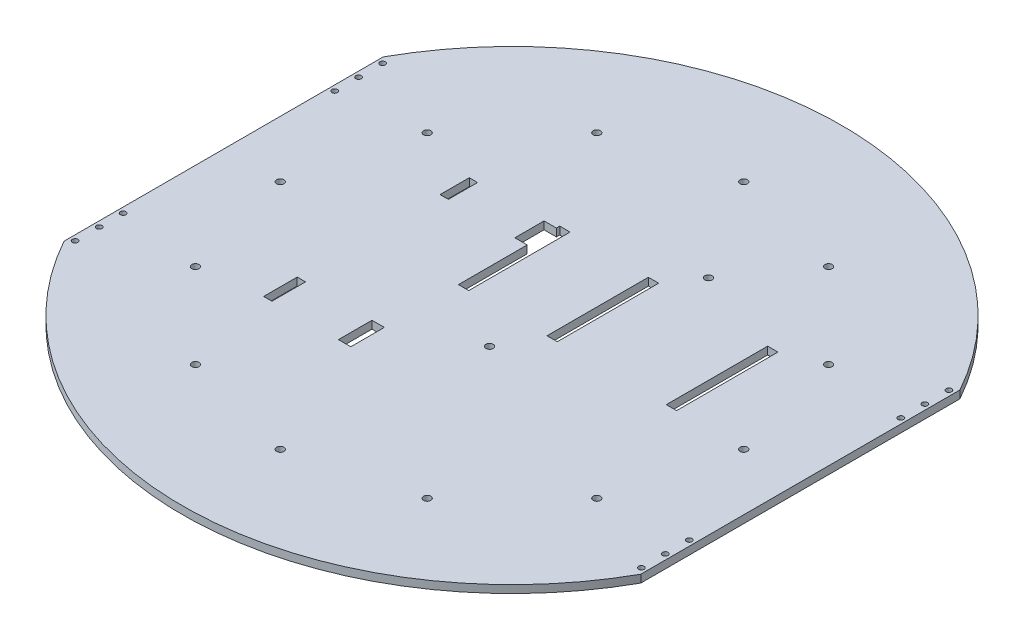
SolidWorks part; units mm, degrees
ref_plane "Front Plane" through (0, 0, 0) normal (0, 0, 1) x (1, 0, 0)
ref_plane "Top Plane" through (0, 0, 0) normal (0, 1, 0) x (1, 0, 0)
ref_plane "Right Plane" through (0, 0, 0) normal (1, 0, 0) x (0, 0, -1)
sketch "Sketch1" plane through (0, 0, 0) normal (0, 1, 0) x (1, 0, 0)
  line L0 (177.8, 98.3738) -> (177.8, -98.3738)
  line L1 (-177.8, 98.3738) -> (-177.8, -98.3738)
  line L2 (0, 0) -> (0, -203.2) construction
  arc A0 (-177.8, -98.3738) -> (177.8, -98.3738) centre (0, 0) ccw
  arc A1 (177.8, 98.3738) -> (-177.8, 98.3738) centre (0, 0) ccw
  dimension "D1" = 406.4
  dimension "D2" = 355.6
extrude "Boss-Extrude1" add sketch "Sketch1" along normal blind 4.7625
sketch "Sketch2" plane through (0, 4.7625, 0) normal (0, 1, 0) x (1, 0, 0)
  line L0 (174.55, -94.8) -> (174.55, -65.2) construction
  line L1 (174.55, 65.2) -> (174.55, 94.8) construction
  line L2 (177.8, -98.3738) -> (177.8, 98.3738) construction
  line L3 (174.55, -80) -> (201.8, -80) construction
  line L4 (201.8, -80) -> (201.8, -130) construction
  point P4 (174.55, 80)
  point P5 (174.55, -80)
  dimension "D1" = 14.8
  dimension "D2" = 14.8
  dimension "D3" = 3.25
  dimension "D4" = 80
  dimension "D5" = 50
  dimension "D6" = 24
  dimension "D7" = 80
hole_wizard "M3 Clearance Hole1" positions "Sketch3" profile "Sketch4" hole size "M3" standard "ANSI Metric" end condition through all
sketch "Sketch3" plane through (0, 4.7625, 0) normal (0, 1, 0) x (1, 0, 0)
  point P0 (174.55, -94.8)
  point P3 (174.55, -80)
  point P5 (174.55, -65.2)
  point P8 (174.55, 65.2)
  point P11 (174.55, 80)
  point P14 (174.55, 94.8)
sketch "Sketch4" plane through (174.55, 4.7625, 94.8) normal (1, 0, 0) x (0, 0, 1)
  line L0 (0, 0) -> (0, 4.7625)
  line L1 (0, 4.7625) -> (1.7, 4.7625)
  line L2 (1.7, 4.7625) -> (1.7, 0)
  line L5 (1.7, 0) -> (0, 0)
  line L11 (0, -6.35) -> (0, 107.95) construction
  dimension "Thru Hole Dia." = 3.4
  dimension "Thru Hole Depth" = 4.7625
mirror "Mirror1" about plane through (0, 0, 0) normal (1, 0, 0) of "M3 Clearance Hole1"
sketch "Sketch5" plane through (0, 4.7625, 0) normal (0, 1, 0) x (1, 0, 0)
  circle A0 centre (0, 0) radius 142.875 construction
  point P3 (0, -142.875)
  dimension "D1" = 285.75
hole_wizard "#8 Clearance Hole1" positions "Sketch6" profile "Sketch7" hole size "#8" standard "ANSI Inch" end condition through all
sketch "Sketch6" plane through (0, 4.7625, 0) normal (0, 1, 0) x (1, 0, 0)
  point P0 (0, -142.875)
sketch "Sketch7" plane through (0, 4.7625, 142.875) normal (1, 0, 0) x (0, 0, 1)
  line L0 (0, 0) -> (0, 4.7625)
  line L1 (0, 4.7625) -> (2.2479, 4.7625)
  line L2 (2.2479, 4.7625) -> (2.2479, 0)
  line L5 (2.2479, 0) -> (0, 0)
  line L11 (0, -6.35) -> (0, 107.95) construction
  dimension "Thru Hole Dia." = 4.4958
  dimension "Thru Hole Depth" = 4.7625
pattern_circular "CirPattern1" count 12 over 360 about axis through (0, 0, 0) along (0, 1, 0) of "#8 Clearance Hole1"
sketch "Sketch8" [suppressed] plane through (0, 4.7625, 0) normal (0, 1, 0) x (1, 0, 0)
  line L0 (-177.8, 0) -> (177.8, 0) construction
  line L1 (-86.43, -7.87) -> (-63.57, -7.87) construction
  line L2 (-86.43, -7.87) -> (-86.43, -56.13) construction
  line L3 (-86.43, -56.13) -> (-63.57, -56.13) construction
  line L4 (-63.57, -7.87) -> (-63.57, -56.13) construction
  line L5 (-86.43, -7.87) -> (-63.57, -56.13) construction
  line L6 (-86.43, -56.13) -> (-63.57, -7.87) construction
  line L7 (-81.35, -87.46) -> (-68.65, -87.46) construction
  line L8 (-81.35, -87.46) -> (-81.35, -92.54) construction
  line L9 (-81.35, -92.54) -> (-68.65, -92.54) construction
  line L10 (-68.65, -87.46) -> (-68.65, -92.54) construction
  line L11 (-81.35, -87.46) -> (-68.65, -92.54) construction
  line L12 (-81.35, -92.54) -> (-68.65, -87.46) construction
  line L13 (-177.8, 98.3738) -> (-177.8, -98.3738) construction
  line L14 (177.8, -98.3738) -> (177.8, 98.3738) construction
  line L15 (-81.35, 87.46) -> (-81.35, 92.54) construction
  line L16 (-81.35, 87.46) -> (-68.65, 92.54) construction
  line L17 (-81.35, 92.54) -> (-68.65, 87.46) construction
  line L18 (-81.35, 87.46) -> (-68.65, 87.46) construction
  line L19 (-68.65, 87.46) -> (-68.65, 92.54) construction
  line L20 (-81.35, 92.54) -> (-68.65, 92.54) construction
  line L21 (-86.43, 56.13) -> (-63.57, 56.13) construction
  line L22 (-86.43, 7.87) -> (-63.57, 56.13) construction
  line L23 (-86.43, 56.13) -> (-63.57, 7.87) construction
  line L24 (-86.43, 7.87) -> (-86.43, 56.13) construction
  line L25 (-86.43, 7.87) -> (-63.57, 7.87) construction
  line L26 (-63.57, 7.87) -> (-63.57, 56.13) construction
  point P0 (-75, -32)
  point P5 (-75, -90)
  dimension "D1" = 75
  dimension "D2" = 32
  dimension "D3" = 90
  dimension "D4" = 48.26
  dimension "D5" = 22.86
  dimension "D6" = 12.7
  dimension "D7" = 5.08
sketch "Sketch11" [suppressed] plane through (0, 4.7625, 0) normal (0, 1, 0) x (1, 0, 0)
  line L0 (-89.97, -4.33) -> (-89.97, -59.67)
  line L1 (-88.97, -5.33) -> (-61.03, -5.33)
  line L2 (-88.97, -5.33) -> (-88.97, -58.67)
  line L3 (-88.97, -58.67) -> (-61.03, -58.67)
  line L4 (-61.03, -5.33) -> (-61.03, -58.67)
  line L5 (-88.97, -5.33) -> (-61.03, -58.67) construction
  line L6 (-88.97, -58.67) -> (-61.03, -5.33) construction
  line L7 (-83.89, -79.84) -> (-66.11, -79.84)
  line L8 (-83.89, -79.84) -> (-83.89, -100.16)
  line L9 (-83.89, -100.16) -> (-66.11, -100.16)
  line L10 (-66.11, -79.84) -> (-66.11, -100.16)
  line L11 (-83.89, -79.84) -> (-66.11, -100.16) construction
  line L12 (-83.89, -100.16) -> (-66.11, -79.84) construction
  line L13 (-89.97, -59.67) -> (-60.03, -59.67)
  line L14 (-60.03, -4.33) -> (-60.03, -59.67)
  line L15 (-89.97, -4.33) -> (-60.03, -4.33)
  line L16 (-84.89, -78.84) -> (-84.89, -101.16)
  line L17 (-84.89, -101.16) -> (-65.11, -101.16)
  line L18 (-65.11, -78.84) -> (-65.11, -101.16)
  line L19 (-84.89, -78.84) -> (-65.11, -78.84)
  line L20 (-177.8, 0) -> (177.8, 0) construction
  line L21 (-177.8, 98.3738) -> (-177.8, -98.3738) construction
  line L22 (177.8, -98.3738) -> (177.8, 98.3738) construction
  line L23 (-83.89, 100.16) -> (-66.11, 79.84) construction
  line L24 (-83.89, 79.84) -> (-66.11, 100.16) construction
  line L25 (-88.97, 58.67) -> (-61.03, 5.33) construction
  line L26 (-88.97, 5.33) -> (-61.03, 58.67) construction
  line L27 (-84.89, 78.84) -> (-65.11, 78.84)
  line L28 (-65.11, 78.84) -> (-65.11, 101.16)
  line L29 (-84.89, 101.16) -> (-65.11, 101.16)
  line L30 (-84.89, 78.84) -> (-84.89, 101.16)
  line L31 (-89.97, 4.33) -> (-60.03, 4.33)
  line L32 (-60.03, 4.33) -> (-60.03, 59.67)
  line L33 (-89.97, 59.67) -> (-60.03, 59.67)
  line L34 (-66.11, 79.84) -> (-66.11, 100.16)
  line L35 (-83.89, 100.16) -> (-66.11, 100.16)
  line L36 (-83.89, 79.84) -> (-83.89, 100.16)
  line L37 (-83.89, 79.84) -> (-66.11, 79.84)
  line L38 (-61.03, 5.33) -> (-61.03, 58.67)
  line L39 (-88.97, 58.67) -> (-61.03, 58.67)
  line L40 (-88.97, 5.33) -> (-88.97, 58.67)
  line L41 (-88.97, 5.33) -> (-61.03, 5.33)
  line L42 (-89.97, 4.33) -> (-89.97, 59.67)
  point P0 (-75, -32)
  point P6 (-75, -90)
  point P35 (-75, 90)
  point P36 (-75, 32)
  dimension "D1" = 17.78
  dimension "D2" = 20.32
  dimension "D3" = 53.34
  dimension "D4" = 27.94
  dimension "D5" = 1
  dimension "D6" = 1
sketch "Sketch12" plane through (0, 4.7625, 0) normal (0, 1, 0) x (1, 0, 0)
  line L0 (-49.13, -46.43) -> (-0.87, -46.43) construction
  line L1 (-0.87, -46.43) -> (-4.045, -112.47) construction
  line L2 (-4.045, -112.47) -> (-45.955, -112.47) construction
  line L3 (-45.955, -112.47) -> (-49.13, -46.43) construction
  line L4 (-25, -46.43) -> (-25, -112.47) construction
  line L5 (0, 0) -> (0, -46.43) construction
  dimension "D1" = 66.04
  dimension "D2" = 46.43
  dimension "D3" = 48.26
  dimension "D4" = 41.91
  dimension "D5" = 25
sketch "Sketch15" plane through (0, 4.7625, 0) normal (0, 1, 0) x (1, 0, 0)
  line L0 (-21.59, 0) -> (27.94, 0) construction
  line L1 (21.59, 62.484) -> (27.94, 62.484)
  line L2 (21.59, 62.484) -> (21.59, 0)
  line L3 (21.59, 0) -> (27.94, 0)
  line L4 (27.94, 62.484) -> (27.94, 0)
  line L5 (27.94, 62.484) -> (27.94, -76.2) construction
  line L6 (-26.67, 122.682) -> (-26.67, -12.7) construction
  line L7 (-26.67, 62.484) -> (-33.02, 62.484)
  line L8 (-26.67, 62.484) -> (-26.67, 0)
  line L9 (-26.67, 0) -> (-33.02, 0)
  line L10 (-33.02, 62.484) -> (-33.02, 60.4029)
  line L11 (95.1484, -81.28) -> (95.1484, 75.184) construction
  line L12 (95.1484, 62.484) -> (101.4984, 62.484)
  line L13 (95.1484, 62.484) -> (95.1484, 0)
  line L14 (95.1484, 0) -> (101.4984, 0)
  line L15 (101.4984, 62.484) -> (101.4984, 0)
  line L16 (-81.64, 67.8) -> (-81.64, -76.2) construction
  line L17 (-81.64, 60.4029) -> (-86.7567, 60.4029)
  line L18 (-81.64, 60.4029) -> (-81.64, 42.402)
  line L19 (-81.64, 42.402) -> (-86.7567, 42.402)
  line L20 (-86.7567, 60.4029) -> (-86.7567, 42.402)
  line L21 (-40.64, -76.2) -> (-40.64, 67.8) construction
  line L22 (-40.64, 60.4029) -> (-33.02, 60.4029)
  line L23 (-40.64, 60.4029) -> (-40.64, 42.402)
  line L24 (-40.64, 42.402) -> (-33.02, 42.402)
  line L26 (-33.02, 42.402) -> (-33.02, 0)
  line L28 (-81.64, -66.3559) -> (-86.7567, -66.3559)
  line L29 (-81.64, -66.3559) -> (-81.64, -45.6717)
  line L30 (-81.64, -45.6717) -> (-86.7567, -45.6717)
  line L31 (-86.7567, -66.3559) -> (-86.7567, -45.6717)
  line L32 (-40.64, -66.3559) -> (-33.02, -66.3559)
  line L33 (-40.64, -66.3559) -> (-40.64, -45.6717)
  line L34 (-40.64, -45.6717) -> (-33.02, -45.6717)
  line L35 (-33.02, -66.3559) -> (-33.02, -45.6717)
extrude "Cut-Extrude1" cut sketch "Sketch15" against normal up to next
sketch "Sketch17" plane through (0, 4.7625, 0) normal (0, 1, 0) x (1, 0, 0)
  circle A0 centre (40.4028, 80.7285) radius 2.2479
  circle A1 centre (9.5383, -23.3764) radius 2.2479
extrude "Cut-Extrude2" cut sketch "Sketch17" against normal up to next
